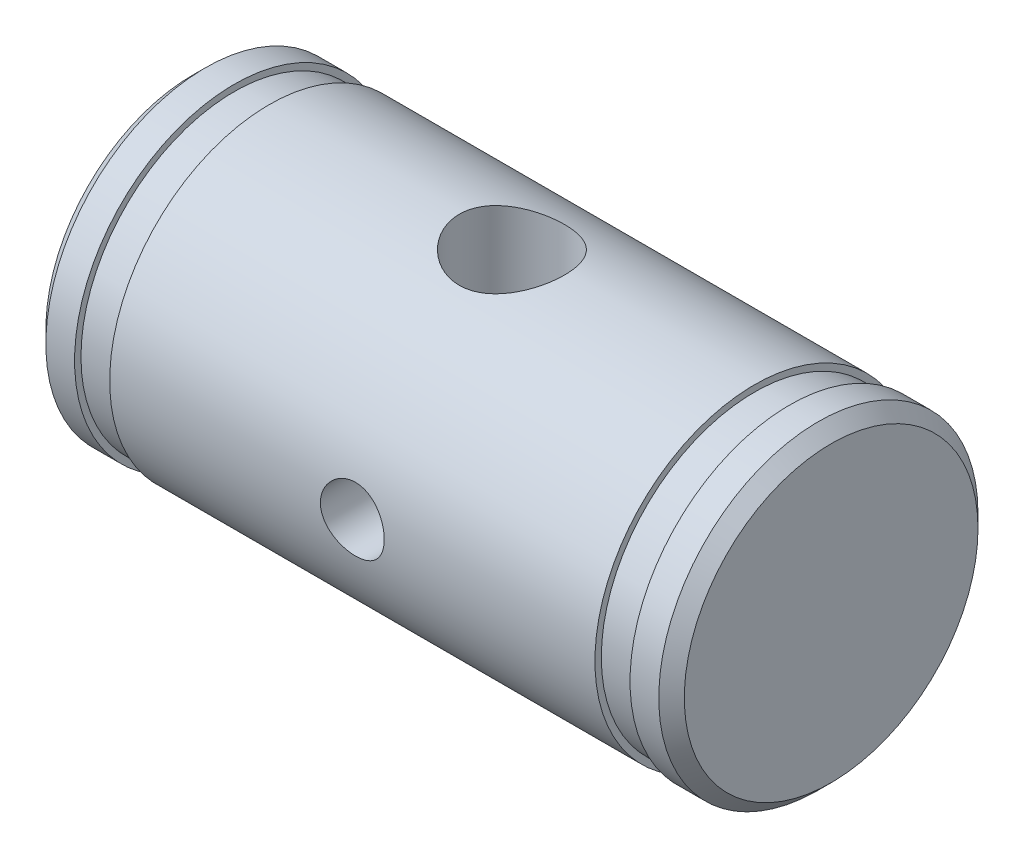
SolidWorks part; units mm, degrees
material "Brass"
ref_plane "Front Plane" through (0, 0, 0) normal (0, 0, 1) x (1, 0, 0)
ref_plane "Top Plane" through (0, 0, 0) normal (0, 1, 0) x (1, 0, 0)
ref_plane "Right Plane" through (0, 0, 0) normal (1, 0, 0) x (0, 0, -1)
sketch "Sketch1" plane through (0, 0, 0) normal (1, 0, 0) x (0, 0, -1)
  circle A0 centre (0, 0) radius 5
  dimension "D1" = 10
extrude "Boss-Extrude1" add sketch "Sketch1" along normal mid plane 20
sketch "Sketch2" plane through (0, 0, 0) normal (0, 1, 0) x (1, 0, 0)
  line L0 (10, 5) -> (-10, 5) construction
  line L1 (-8.7, 5) -> (-7.6, 5)
  line L2 (-8.7, 5) -> (-8.7, 4.8)
  line L3 (-8.7, 4.8) -> (-7.6, 4.8)
  line L4 (-7.6, 5) -> (-7.6, 4.8)
  line L5 (0, 0) -> (-10, 0) construction
  line L6 (-10, 5) -> (-10, -5) construction
  dimension "D1" = 1.1
  dimension "D2" = 4.8
  dimension "D3" = 7.6
revolve "Cut-Revolve1" cut sketch "Sketch2" angle 360 about L5
mirror "Mirror1" about plane through (0, 0, 0) normal (1, 0, 0) of "Cut-Revolve1"
chamfer "Chamfer1" distance 0.4 angle 45 2 edges at (10, 0, -5) (-10, 0, -5)
ref_plane "Plane1" through (0, 5, 0) normal (0, 1, 0) x (1, 0, 0)
hole_wizard "M4 Tapped Hole4" positions "Sketch4" profile "Sketch5" tap size "M4" standard "ISO" end condition through all
sketch "Sketch4" plane through (0, 5, 0) normal (0, 1, 0) x (1, 0, 0)
  point P2 (0, 0)
  point P6 (0, 0)
  point P11 (0, 0)
sketch "Sketch5" plane through (0, 5, 0) normal (1, 0, 0) x (0, 0, 1)
  line L0 (0, 0) -> (0, 10)
  line L1 (0, 10) -> (1.65, 10)
  line L2 (1.65, 10) -> (1.65, 0)
  line L5 (1.65, 0) -> (0, 0)
  line L11 (0, -6.35) -> (0, 107.95) construction
  dimension "Thru Tap Drill Dia." = 3.3
  dimension "Thru Tap Drill Depth" = 10
cosmetic thread "Hole Thread1" parameters "D2"=4
ref_plane "Plane2" through (0, 0, -5) normal (0, 0, -1) x (-1, 0, 0)
sketch "Sketch6" plane through (0, 0, -5) normal (0, 0, -1) x (-1, 0, 0)
  circle A0 centre (0, 0) radius 1
  dimension "D1" = 2
extrude "Cut-Extrude1" cut sketch "Sketch6" against normal through all
